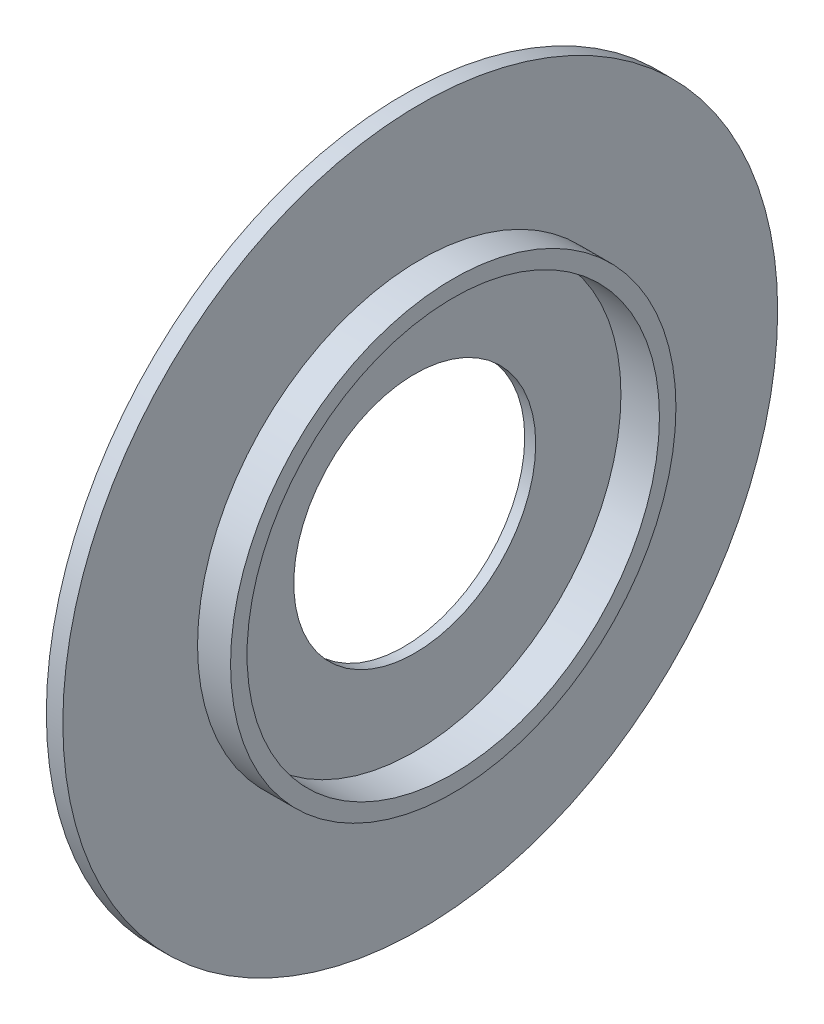
SolidWorks part; units mm, degrees
material "ABS"
ref_plane "Front Plane" through (0, 0, 0) normal (0, 0, 1) x (1, 0, 0)
ref_plane "Top Plane" through (0, 0, 0) normal (0, 1, 0) x (1, 0, 0)
ref_plane "Right Plane" through (0, 0, 0) normal (1, 0, 0) x (0, 0, -1)
sketch "Sketch1" plane through (72, 0, 0) normal (1, 0, 0) x (0, 0, -1)
  circle A0 centre (50, -18.3727) radius 65
  arc A1 (50, 46.3864) -> (50, -83.1319) centre (50, -18.3727) ccw construction
  dimension "D1" = 130
extrude "BULK EXTRUDE" add sketch "Sketch1" along normal blind 3
sketch "Sketch2" plane through (75, 0, 0) normal (1, 0, 0) x (0, 0, -1)
  circle A0 centre (50, -18.3727) radius 37.5
  circle A1 centre (50, -18.3727) radius 65 construction
  circle A2 centre (50, -18.3727) radius 40.5
  dimension "D1" = 75
  dimension "D2" = 3
extrude "BEARING RING" add sketch "Sketch2" along normal blind 6
sketch "Sketch4" plane through (75, 0, 0) normal (1, 0, 0) x (0, 0, -1)
  circle A1 centre (50, -18.3727) radius 37.5
  circle A2 centre (50, -18.3727) radius 37.5
  dimension "D1" = 0
extrude "BEARING CUT" cut sketch "Sketch4" against normal blind 1
sketch "Sketch5" plane through (74, 0, 0) normal (1, 0, 0) x (0, 0, -1)
  circle A0 centre (50, -18.3727) radius 22
  circle A1 centre (50, -18.3727) radius 37.5 construction
  dimension "D1" = 44
extrude "WIRE PASSTHRU CUT" cut sketch "Sketch5" against normal through all
